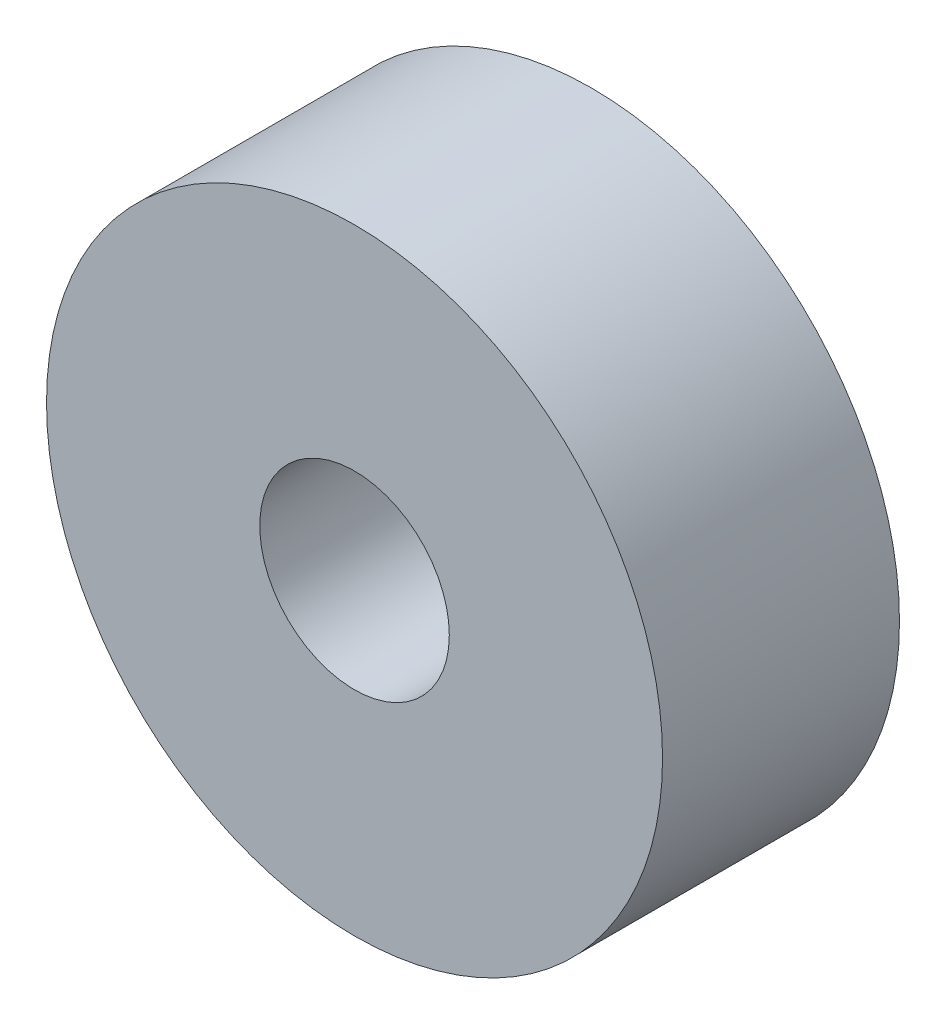
SolidWorks part; units mm, degrees
ref_plane "Plan de face" through (0, 0, 0) normal (0, 0, 1) x (1, 0, 0)
ref_plane "Plan de dessus" through (0, 0, 0) normal (0, 1, 0) x (1, 0, 0)
ref_plane "Plan de droite" through (0, 0, 0) normal (1, 0, 0) x (0, 0, -1)
sketch "Esquisse1" plane through (0, 0, 0) normal (0, 0, 1) x (1, 0, 0)
  circle A0 centre (0, 0) radius 6.5
  circle A1 centre (0, 0) radius 2
extrude "Boss.-Extru.1" add sketch "Esquisse1" along normal blind 5
